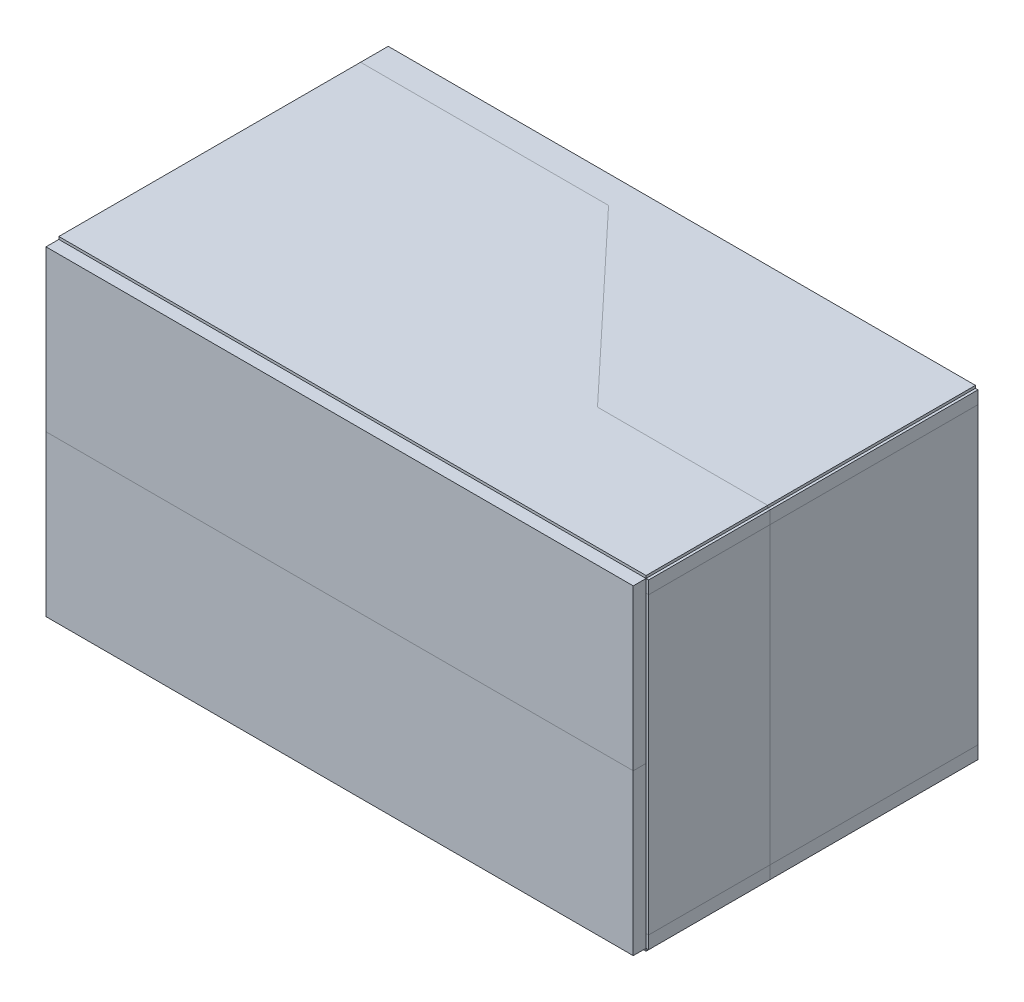
SolidWorks part; units mm, degrees
other "바닥"
other "우측면"
other "정면"
other "좌측면"
other "천장1"
other "천장2"
other "후면"
other "하단인테리어1"
other "상단인테리어1"
other "후면상단작음1"
other "후면하단작음1"
other "후면상단큼1"
other "후면하단큼1"
other "하단인테리어2"
other "상단인테리어2"
other "후면상단작음2"
other "후면하단작음2"
ref_plane "정면" through (0, 0, 0) normal (0, 0, 1) x (1, 0, 0)
ref_plane "윗면" through (0, 0, 0) normal (0, 1, 0) x (1, 0, 0)
ref_plane "우측면" through (0, 0, 0) normal (1, 0, 0) x (0, 0, -1)
sketch "스케치1" plane through (0, 0, 0) normal (0, 0, 1) x (1, 0, 0)
  line L1 (51, 74.896) -> (280, 74.896)
  line L2 (51, 74.896) -> (51, -50)
  line L3 (51, -50) -> (280, -50)
  line L4 (280, 74.896) -> (280, -50)
extrude "보스-돌출1" add sketch "스케치1" along normal up to surface (7.8606 mm away)
sketch "스케치2" plane through (0, 0, 7.8606) normal (0, 0, 1) x (1, 0, 0)
  line L0 (280, 74.896) -> (280, -50) construction
  line L1 (51, 74.896) -> (280, 74.896)
  line L2 (51, 74.896) -> (51, 69.896)
  line L3 (51, 69.896) -> (280, 69.896)
  line L4 (280, 74.896) -> (280, 69.896)
  dimension "D1" = 5
extrude "컷-돌출1" cut sketch "스케치2" against normal up to surface (7.8606 mm away) contours L1 L3 L2 up to face at (165.5, 12.448, 0)
sketch "스케치4" plane through (0, 0, 7.8606) normal (0, 0, 1) x (1, 0, 0)
  line L0 (280, 69.896) -> (280, -50) construction
  line L1 (51, -50) -> (280, -50)
  line L2 (51, -50) -> (51, -45)
  line L3 (51, -45) -> (280, -45)
  line L4 (280, -50) -> (280, -45)
  line M1 (280, -50) -> (280, 69.896)
  line M3 (51, 69.896) -> (51, -50)
  line M4 (51, -50) -> (280, -50)
  dimension "D1" = 5
extrude "컷-돌출2" cut sketch "스케치4" against normal up to surface (7.8606 mm away) contours L3 M3 M4 M1 up to face at (165.5, 9.948, 0)
sketch "스케치5" plane through (0, 0, 7.8606) normal (0, 0, 1) x (1, 0, 0)
  line L0 (51, -45) -> (280, -45) construction
  line L1 (280, 69.896) -> (275, 69.896)
  line L2 (280, 69.896) -> (280, -45)
  line L3 (280, -45) -> (275, -45)
  line L4 (275, 69.896) -> (275, -45)
  line M1 (51, -45) -> (280, -45)
  line M2 (280, -45) -> (280, 69.896)
  line M3 (280, 69.896) -> (51, 69.896)
  dimension "D1" = 5
extrude "컷-돌출3" cut sketch "스케치5" against normal up to surface (7.8606 mm away) contours L4 M3 M1 M2 up to face at (165.5, 12.448, 0)
sketch "스케치6" plane through (0, 69.896, 0) normal (0, 1, 0) x (1, 0, 0)
  line L1 (51, 0) -> (280, 0)
  line L2 (51, 0) -> (51, -128.4421)
  line L3 (51, -128.4421) -> (280, -128.4421)
  line L4 (280, 0) -> (280, -128.4421)
extrude "보스-돌출3" add sketch "스케치6" along normal blind 5 separate body
sketch "스케치7" plane through (0, 0, 7.8606) normal (0, 0, 1) x (1, 0, 0)
  line L0 (51, -45) -> (275, -45) construction
  line L1 (51, 69.896) -> (56, 69.896)
  line L2 (51, 69.896) -> (51, -45)
  line L3 (51, -45) -> (56, -45)
  line L4 (56, 69.896) -> (56, -45)
  dimension "D1" = 5
extrude "보스-돌출4" add sketch "스케치7" along normal up to surface (120.5815 mm away) separate body up to face at (165.5, 72.396, 128.4421)
sketch "스케치8" plane through (0, -45, 0) normal (0, -1, 0) x (1, 0, 0)
  line L1 (51, 128.4421) -> (280, 128.4421)
  line L2 (51, 128.4421) -> (51, 0)
  line L3 (51, 0) -> (280, 0)
  line L4 (280, 128.4421) -> (280, 0)
extrude "보스-돌출5" add sketch "스케치8" along normal blind 5 separate body
sketch "스케치9" plane through (0, 0, 128.4421) normal (0, 0, 1) x (1, 0, 0)
  line L1 (51, 74.896) -> (280, 74.896)
  line L2 (51, 74.896) -> (51, 12.446)
  line L3 (51, 12.446) -> (280, 12.446)
  line L4 (280, 74.896) -> (280, 12.446)
  dimension "D1" = 62.45
extrude "보스-돌출6" add sketch "스케치9" along normal blind 5 separate body
sketch "스케치10" plane through (0, 0, 128.4421) normal (0, 0, 1) x (1, 0, 0)
  line L1 (51, 12.446) -> (280, 12.446)
  line L2 (51, 12.446) -> (51, -50)
  line L3 (51, -50) -> (280, -50)
  line L4 (280, 12.446) -> (280, -50)
extrude "보스-돌출7" add sketch "스케치10" along normal blind 5 separate body
sketch "스케치11" plane through (275, 0, 0) normal (1, 0, 0) x (0, 0, -1)
  line L1 (0, -45) -> (-128.4421, -45)
  line L2 (0, -45) -> (0, 69.896)
  line L3 (0, 69.896) -> (-128.4421, 69.896)
  line L4 (-128.4421, -45) -> (-128.4421, 69.896)
extrude "보스-돌출8" add sketch "스케치11" along normal blind 5 separate body
sketch "스케치12" plane through (0, -50, 0) normal (0, -1, 0) x (1, 0, 0)
  line L0 (51, 10.7712) -> (147.7059, 10.7712)
  line L1 (51, 128.4421) -> (51, 0) construction
  line L2 (147.7059, 10.7712) -> (213.6585, 81.0356)
  line L3 (213.6585, 81.0356) -> (280, 81.0356)
  line L4 (280, 0) -> (280, 128.4421) construction
  line L5 (51, 10.7712) -> (51, 0)
  line L6 (51, 0) -> (280, 0)
  line L7 (280, 0) -> (280, 81.0356)
extrude "보스-돌출9" add sketch "스케치12" along normal blind 1 separate body
sketch "스케치13" plane through (0, -50, 0) normal (0, -1, 0) x (1, 0, 0)
  line L0 (51, 128.4421) -> (51, 10.7712)
  line L1 (51, 10.7712) -> (147.7059, 10.7712)
  line L2 (147.7059, 10.7712) -> (213.6585, 81.0356)
  line L3 (213.6585, 81.0356) -> (280, 81.0356)
  line L4 (280, 81.0356) -> (280, 128.4421)
  line L5 (280, 128.4421) -> (51, 128.4421)
extrude "보스-돌출10" add sketch "스케치13" along normal blind 1 separate body
sketch "스케치14" plane through (280, 0, 0) normal (1, 0, 0) x (0, 0, -1)
  line L1 (-81.0356, -50) -> (-128.4421, -50)
  line L2 (-81.0356, -50) -> (-81.0356, -45)
  line L3 (-81.0356, -45) -> (-128.4421, -45)
  line L4 (-128.4421, -50) -> (-128.4421, -45)
extrude "보스-돌출11" add sketch "스케치14" along normal blind 1 separate body
sketch "스케치15" plane through (280, 0, 0) normal (1, 0, 0) x (0, 0, -1)
  line L1 (-81.0356, -50) -> (0, -50)
  line L2 (-81.0356, -50) -> (-81.0356, -45)
  line L3 (-81.0356, -45) -> (0, -45)
  line L4 (0, -50) -> (0, -45)
extrude "보스-돌출12" add sketch "스케치15" along normal blind 1 separate body
sketch "스케치16" plane through (280, 0, 0) normal (1, 0, 0) x (0, 0, -1)
  line L0 (-128.4421, 69.896) -> (0, 69.896) construction
  line L1 (-128.4421, -45) -> (-81.0356, -45)
  line L2 (-128.4421, -45) -> (-128.4421, 69.896)
  line L3 (-128.4421, 69.896) -> (-81.0356, 69.896)
  line L4 (-81.0356, -45) -> (-81.0356, 69.896)
extrude "보스-돌출13" add sketch "스케치16" along normal blind 1 separate body
sketch "스케치17" plane through (280, 0, 0) normal (1, 0, 0) x (0, 0, -1)
  line L0 (0, 74.896) -> (0, 69.896) construction
  line L1 (-81.0356, -45) -> (0, -45)
  line L2 (-81.0356, -45) -> (-81.0356, 69.896)
  line L3 (-81.0356, 69.896) -> (0, 69.896)
  line L4 (0, -45) -> (0, 69.896)
  line L5 (-128.4421, 69.896) -> (0, 69.896) construction
extrude "보스-돌출14" add sketch "스케치17" along normal blind 1 separate body
ref_plane "평면1" through (0, 12.446, 0) normal (0, 1, 0) x (1, 0, 0)
mirror "대칭 복사2" about plane through (0, 12.446, 0) normal (0, 1, 0) of bodies 112 113 114 115
other "바디 저장1"
other "바디 저장2"
sketch "스케치18" plane through (0, 0, 7.8606) normal (0, 0, 1) x (1, 0, 0)
  line L0 (51, 69.896) -> (275, 69.896) construction
  line L1 (56, 69.896) -> (109.127, 69.896)
  line L2 (56, 69.896) -> (56, 46.8524)
  line L3 (56, 46.8524) -> (109.127, 46.8524)
  line L4 (109.127, 69.896) -> (109.127, 46.8524)
  line L5 (118.0366, 69.896) -> (158.4268, 69.896)
  line L6 (118.0366, 69.896) -> (118.0366, 46.8524)
  line L7 (118.0366, 46.8524) -> (158.4268, 46.8524)
  line L8 (158.4268, 69.896) -> (158.4268, 46.8524)
  line L9 (51, 69.896) -> (280, 69.896) construction
  line L10 (165.5, 69.896) -> (199.5595, 69.896)
  line L11 (165.5, 69.896) -> (165.5, 46.8524)
  line L12 (165.5, 46.8524) -> (199.5595, 46.8524)
  line L13 (199.5595, 69.896) -> (199.5595, 46.8524)
  line L14 (56, 69.896) -> (56, -45) construction
  line L15 (206.8357, 69.896) -> (247.9684, 69.896)
  line L16 (206.8357, 69.896) -> (206.8357, 46.8524)
  line L17 (206.8357, 46.8524) -> (247.9684, 46.8524)
  line L18 (247.9684, 69.896) -> (247.9684, 46.8524)
  line L19 (56, 39.2792) -> (90.5653, 39.2792)
  line L20 (56, 39.2792) -> (56, 12.448)
  line L21 (56, 12.448) -> (90.5653, 12.448)
  line L22 (90.5653, 39.2792) -> (90.5653, 12.448)
  line L24 (95.7626, 39.2792) -> (126.9462, 39.2792)
  line L25 (95.7626, 39.2792) -> (95.7626, 12.448)
  line L26 (95.7626, 12.448) -> (126.9462, 12.448)
  line L27 (126.9462, 39.2792) -> (126.9462, 12.448)
  line L28 (135.8558, 39.2792) -> (184.2647, 39.2792)
  line L29 (135.8558, 39.2792) -> (135.8558, -2.7445)
  line L30 (135.8558, -2.7445) -> (184.2647, -2.7445)
  line L31 (184.2647, 39.2792) -> (184.2647, -2.7445)
  line L32 (189.462, 39.2792) -> (199.5595, 39.2792)
  line L33 (189.462, 39.2792) -> (189.462, 27.2512)
  line L34 (189.462, 27.2512) -> (199.5595, 27.2512)
  line L35 (199.5595, 39.2792) -> (199.5595, 27.2512)
  line L36 (206.8357, 39.2792) -> (263.5602, 39.2792)
  line L37 (206.8357, 39.2792) -> (206.8357, 13.4413)
  line L38 (206.8357, 13.4413) -> (263.5602, 13.4413)
  line L39 (263.5602, 39.2792) -> (263.5602, 13.4413)
  line L40 (56, 3.9377) -> (126.9462, 3.9377)
  line L41 (56, 3.9377) -> (56, -20.5637)
  line L42 (56, -20.5637) -> (126.9462, -20.5637)
  line L43 (126.9462, 3.9377) -> (126.9462, -20.5637)
  line L44 (130.2131, -5.1204) -> (194.5108, -5.1204)
  line L45 (130.2131, -5.1204) -> (130.2131, -31.8492)
  line L46 (130.2131, -31.8492) -> (194.5108, -31.8492)
  line L47 (194.5108, -5.1204) -> (194.5108, -31.8492)
  line L48 (187.977, 11.0654) -> (263.5602, 11.0654)
  line L49 (187.977, 11.0654) -> (187.977, -2.7445)
  line L50 (187.977, -2.7445) -> (263.5602, -2.7445)
  line L51 (263.5602, 11.0654) -> (263.5602, -2.7445)
  line L52 (199.5595, -7.1993) -> (263.5602, -7.1993)
  line L53 (199.5595, -7.1993) -> (199.5595, -41.5013)
  line L54 (199.5595, -41.5013) -> (263.5602, -41.5013)
  line L55 (263.5602, -7.1993) -> (263.5602, -41.5013)
  line L56 (58.6392, -27.8399) -> (81.5072, -27.8399)
  line L57 (58.6392, -27.8399) -> (58.6392, -41.5013)
  line L58 (58.6392, -41.5013) -> (81.5072, -41.5013)
  line L59 (81.5072, -27.8399) -> (81.5072, -41.5013)
  line L60 (97.2475, -29.9188) -> (121.4519, -29.9188)
  line L61 (97.2475, -29.9188) -> (97.2475, -41.5013)
  line L62 (97.2475, -41.5013) -> (121.4519, -41.5013)
  line L63 (121.4519, -29.9188) -> (121.4519, -41.5013)
extrude "보스-돌출15" add sketch "스케치18" along normal blind 20 separate body
sketch "스케치19" plane through (0, 0, 27.8606) normal (0, 0, 1) x (1, 0, 0)
  line L0 (206.8357, 69.896) -> (206.8357, 46.8524) construction
  line L1 (59.7235, 66.6576) -> (101.2833, 66.6576)
  line L2 (59.7235, 66.6576) -> (59.7235, 34.1197)
  line L3 (59.7235, 34.1197) -> (101.2833, 34.1197)
  line L4 (101.2833, 66.6576) -> (101.2833, 34.1197)
  line L5 (107.7908, 64.8828) -> (163.8448, 64.8828)
  line L6 (107.7908, 64.8828) -> (107.7908, 39.2962)
  line L7 (107.7908, 39.2962) -> (163.8448, 39.2962)
  line L8 (163.8448, 64.8828) -> (163.8448, 39.2962)
  line L9 (173.9019, 63.6996) -> (194.6079, 63.6996)
  line L10 (173.9019, 63.6996) -> (173.9019, 22.1398)
  line L11 (173.9019, 22.1398) -> (194.6079, 22.1398)
  line L12 (194.6079, 63.6996) -> (194.6079, 22.1398)
  line L13 (206.8357, 66.6576) -> (254.3593, 66.6576)
  line L14 (206.8357, 66.6576) -> (206.8357, 32.4928)
  line L15 (206.8357, 32.4928) -> (254.3593, 32.4928)
  line L16 (254.3593, 66.6576) -> (254.3593, 32.4928)
  line L17 (58.6392, -41.5013) -> (81.5072, -41.5013) construction
  line L18 (66.379, 25.9852) -> (133.0817, 25.9852)
  line L19 (66.379, 25.9852) -> (66.379, -6.8485)
  line L20 (66.379, -6.8485) -> (133.0817, -6.8485)
  line L21 (133.0817, 25.9852) -> (133.0817, -6.8485)
  line L22 (148.6111, 18.2944) -> (189.7272, 18.2944)
  line L23 (148.6111, 18.2944) -> (148.6111, -28.8855)
  line L24 (148.6111, -28.8855) -> (189.7272, -28.8855)
  line L25 (189.7272, 18.2944) -> (189.7272, -28.8855)
  line L26 (201.5592, 21.1045) -> (258.5005, 21.1045)
  line L27 (201.5592, 21.1045) -> (201.5592, -32.8788)
  line L28 (201.5592, -32.8788) -> (258.5005, -32.8788)
  line L29 (258.5005, 21.1045) -> (258.5005, -32.8788)
  line L30 (133.0817, -14.5393) -> (64.4563, -14.5393)
  line L31 (133.0817, -14.5393) -> (133.0817, -41.5013)
  line L32 (133.0817, -41.5013) -> (64.4563, -41.5013)
  line L33 (64.4563, -14.5393) -> (64.4563, -41.5013)
extrude "보스-돌출16" add sketch "스케치19" along normal blind 20 separate body
sketch "스케치20" plane through (0, 0, 47.8606) normal (0, 0, 1) x (1, 0, 0)
  line L0 (184.2647, -2.7445) -> (184.2647, 39.2792) construction
  line L1 (70.0732, 56.5044) -> (115.3637, 56.5044)
  line L2 (70.0732, 56.5044) -> (70.0732, 11.3624)
  line L3 (70.0732, 11.3624) -> (115.3637, 11.3624)
  line L4 (115.3637, 56.5044) -> (115.3637, 11.3624)
  line L5 (121.0065, 67.6415) -> (180.5524, 67.6415)
  line L6 (121.0065, 67.6415) -> (121.0065, 15.3717)
  line L7 (121.0065, 15.3717) -> (180.5524, 15.3717)
  line L8 (180.5524, 67.6415) -> (180.5524, 15.3717)
  line L9 (186.1951, 67.6415) -> (240.6922, 67.6415)
  line L10 (186.1951, 67.6415) -> (186.1951, 39.5762)
  line L11 (186.1951, 39.5762) -> (240.6922, 39.5762)
  line L12 (240.6922, 67.6415) -> (240.6922, 39.5762)
  line L13 (245.8895, 67.6415) -> (269.0545, 67.6415)
  line L14 (245.8895, 67.6415) -> (245.8895, 10.1745)
  line L15 (245.8895, 10.1745) -> (269.0545, 10.1745)
  line L16 (269.0545, 67.6415) -> (269.0545, 10.1745)
  line L17 (61.609, 2.1558) -> (117.4426, 2.1558)
  line L18 (61.609, 2.1558) -> (61.609, -35.2646)
  line L19 (61.609, -35.2646) -> (117.4426, -35.2646)
  line L20 (117.4426, 2.1558) -> (117.4426, -35.2646)
  line L21 (123.0854, 6.9076) -> (176.84, 6.9076)
  line L22 (123.0854, 6.9076) -> (123.0854, -36.601)
  line L23 (123.0854, -36.601) -> (176.84, -36.601)
  line L24 (176.84, 6.9076) -> (176.84, -36.601)
  line L25 (184.2647, 29.0331) -> (204.1628, 29.0331)
  line L26 (184.2647, 29.0331) -> (184.2647, -35.2646)
  line L27 (184.2647, -35.2646) -> (204.1628, -35.2646)
  line L28 (204.1628, 29.0331) -> (204.1628, -35.2646)
  line L30 (212.1815, 26.0633) -> (235.9405, 26.0633)
  line L31 (212.1815, 26.0633) -> (212.1815, -36.601)
  line L32 (212.1815, -36.601) -> (235.9405, -36.601)
  line L33 (235.9405, 26.0633) -> (235.9405, -36.601)
  line L34 (243.2166, -5.2689) -> (272.7668, -5.2689)
  line L35 (243.2166, -5.2689) -> (243.2166, -36.601)
  line L36 (243.2166, -36.601) -> (272.7668, -36.601)
  line L37 (272.7668, -5.2689) -> (272.7668, -36.601)
extrude "보스-돌출17" add sketch "스케치20" along normal blind 30 separate body
sketch "스케치21" plane through (0, 0, 77.8606) normal (0, 0, 1) x (1, 0, 0)
  line L0 (61.609, -35.2646) -> (117.4426, -35.2646) construction
  line L1 (58.6392, 67.6415) -> (83.1406, 67.6415)
  line L2 (58.6392, 67.6415) -> (58.6392, 41.8036)
  line L3 (58.6392, 41.8036) -> (83.1406, 41.8036)
  line L4 (83.1406, 67.6415) -> (83.1406, 41.8036)
  line L5 (59.8271, 29.4786) -> (95.4656, 29.4786)
  line L6 (59.8271, 29.4786) -> (59.8271, -4.0809)
  line L7 (59.8271, -4.0809) -> (95.4656, -4.0809)
  line L8 (95.4656, 29.4786) -> (95.4656, -4.0809)
  line L9 (93.6837, 63.9291) -> (136.8953, 63.9291)
  line L10 (93.6837, 63.9291) -> (93.6837, 32.894)
  line L11 (93.6837, 32.894) -> (136.8953, 32.894)
  line L12 (136.8953, 63.9291) -> (136.8953, 32.894)
  line L13 (109.8694, 23.2419) -> (150.7052, 23.2419)
  line L14 (109.8694, 23.2419) -> (109.8694, -19.8212)
  line L15 (109.8694, -19.8212) -> (150.7052, -19.8212)
  line L16 (150.7052, 23.2419) -> (150.7052, -19.8212)
  line L17 (58.6392, -15.0694) -> (105.7116, -15.0694)
  line L18 (58.6392, -15.0694) -> (58.6392, -35.2646)
  line L19 (58.6392, -35.2646) -> (105.7116, -35.2646)
  line L20 (105.7116, -15.0694) -> (105.7116, -35.2646)
  line L22 (155.16, 59.4743) -> (193.9168, 59.4743)
  line L23 (155.16, 59.4743) -> (155.16, 12.6989)
  line L24 (155.16, 12.6989) -> (193.9168, 12.6989)
  line L25 (193.9168, 59.4743) -> (193.9168, 12.6989)
  line L26 (206.6872, 61.9987) -> (262.6693, 61.9987)
  line L27 (206.6872, 61.9987) -> (206.6872, 29.4786)
  line L28 (206.6872, 29.4786) -> (262.6693, 29.4786)
  line L29 (262.6693, 61.9987) -> (262.6693, 29.4786)
extrude "보스-돌출18" add sketch "스케치21" along normal blind 30 separate body
